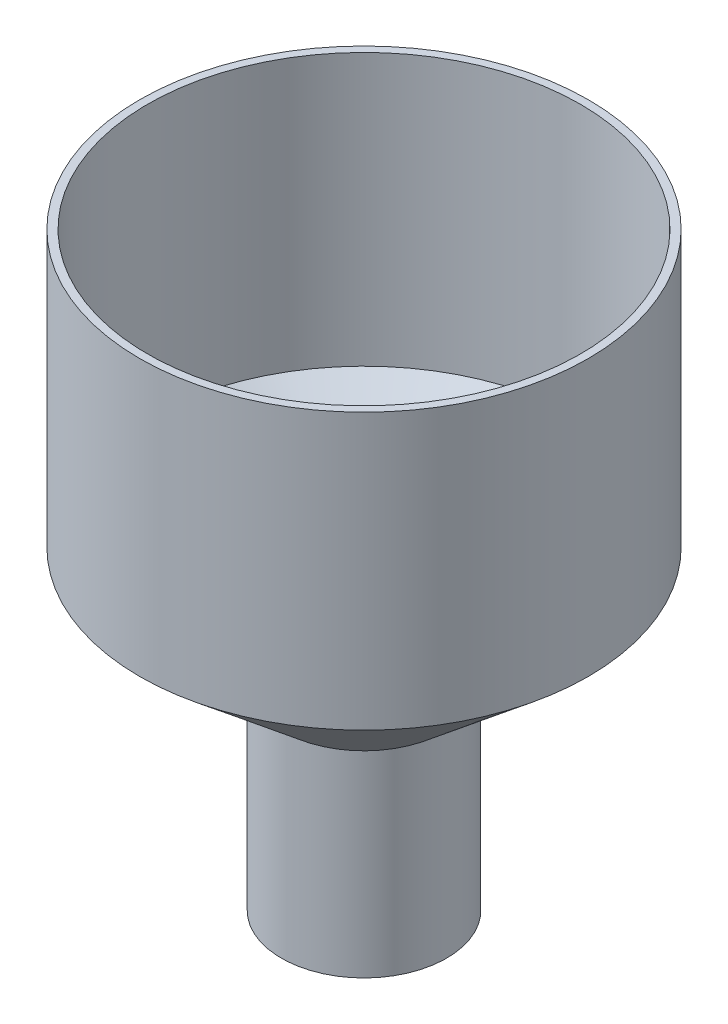
SolidWorks part; units mm, degrees
ref_plane "Front Plane" through (0, 0, 0) normal (0, 0, 1) x (1, 0, 0)
ref_plane "Top Plane" through (0, 0, 0) normal (0, 1, 0) x (1, 0, 0)
ref_plane "Right Plane" through (0, 0, 0) normal (1, 0, 0) x (0, 0, -1)
sketch "Sketch1" plane through (0, 0, 0) normal (0, 0, 1) x (1, 0, 0)
  line L0 (0, 0) -> (0, 140.4291) construction
  line L1 (19, -26.6693) -> (19, 24.2675)
  line L2 (19, 24.2675) -> (55, 54.2675)
  line L3 (55, 54.2675) -> (55, 123.3307)
  line L4 (55, 123.3307) -> (57, 123.3307)
  line L5 (57, 123.3307) -> (57, 53.3307)
  line L6 (57, 53.3307) -> (21, 23.3307)
  line L7 (21, 23.3307) -> (21, -26.6693)
  line L8 (21, -26.6693) -> (19, -26.6693)
  dimension "D1" = 57
  dimension "D2" = 2
  dimension "D3" = 2
  dimension "D4" = 2
  dimension "D5" = 50
  dimension "D6" = 70
  dimension "D7" = 30
  dimension "D8" = 21
revolve "Revolve1" add sketch "Sketch1" angle 360 about L0
